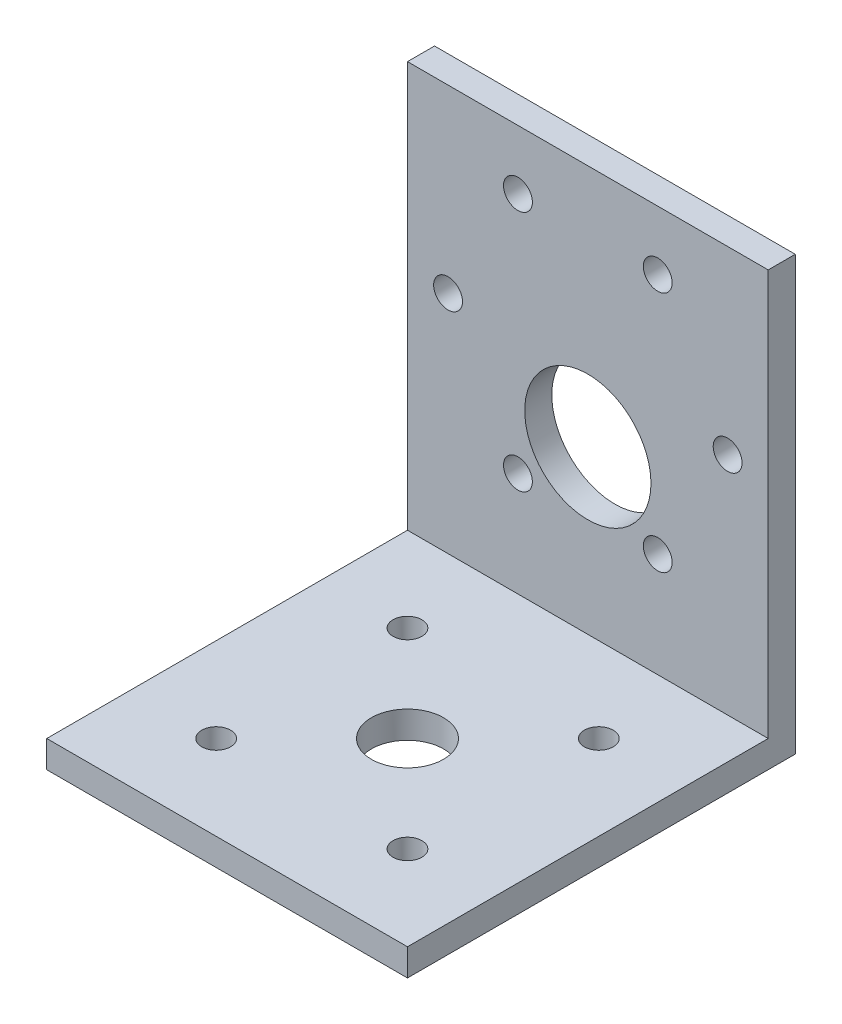
SolidWorks part; units mm, degrees
ref_plane "Front Plane" through (0, 0, 0) normal (0, 0, 1) x (1, 0, 0)
ref_plane "Top Plane" through (0, 0, 0) normal (0, 1, 0) x (1, 0, 0)
ref_plane "Right Plane" through (0, 0, 0) normal (1, 0, 0) x (0, 0, -1)
sketch "Sketch2" plane through (0, 0, 0) normal (0, 0, 1) x (1, 0, 0)
  line L0 (47.0148, -20) -> (-7.0148, -20) construction
  line L1 (0, 0) -> (40, 0)
  line L2 (0, 0) -> (0, -45)
  line L3 (0, -45) -> (40, -45)
  line L4 (40, 0) -> (40, -45)
  line L5 (20, -20) -> (20, -27) construction
  circle A0 centre (4.5, -20) radius 1.6
  circle A1 centre (35.5, -20) radius 1.6
  circle A3 centre (12.25, -6.5766) radius 1.6
  circle A4 centre (27.75, -6.5766) radius 1.6
  circle A5 centre (27.75, -33.4234) radius 1.6
  circle A6 centre (12.25, -33.4234) radius 1.6
  circle A7 centre (20, -27) radius 7
  dimension "D2" = 7
  dimension "D3" = 3.2
  dimension "D5" = 14
  dimension "D1" = 40
  dimension "D4" = 15.5
  dimension "D6" = 20
  dimension "D7" = 45
extrude "Boss-Extrude1" add sketch "Sketch2" along normal blind 3
sketch "Sketch3" plane through (0, 0, 0) normal (1, 0, 0) x (0, 0, -1)
  line L1 (0, -45) -> (-43, -45)
  line L2 (0, -45) -> (0, -48)
  line L3 (0, -48) -> (-43, -48)
  line L4 (-43, -45) -> (-43, -48)
  dimension "D1" = 3
  dimension "D2" = 43
extrude "Boss-Extrude2" add sketch "Sketch3" along normal up to surface (40 mm away) up to face at (40, -22.5, 1.5)
sketch "Sketch4" plane through (0, -45, 0) normal (0, 1, 0) x (1, 0, 0)
  line L0 (20, -3) -> (20, -43) construction
  line L1 (0, -3) -> (40, -3) construction
  line L2 (40, -43) -> (0, -43) construction
  line L4 (0, -3) -> (0, -43) construction
  line L6 (40, -3) -> (0, -43) construction
  circle A0 centre (9.3934, -33.6066) radius 1.6
  circle A1 centre (20, -23) radius 4
  circle A2 centre (9.3934, -12.3934) radius 1.6
  circle A3 centre (30.6066, -12.3934) radius 1.6
  circle A4 centre (30.6066, -33.6066) radius 1.6
  point P10 (0, 0)
  point P14 (20, -23)
  point P25 (20, -23)
  dimension "D3" = 8
  dimension "D4" = 3.2
  dimension "D1" = 15
  dimension "D2" = 4
extrude "Cut-Extrude1" cut sketch "Sketch4" against normal through all both and the other way through all
